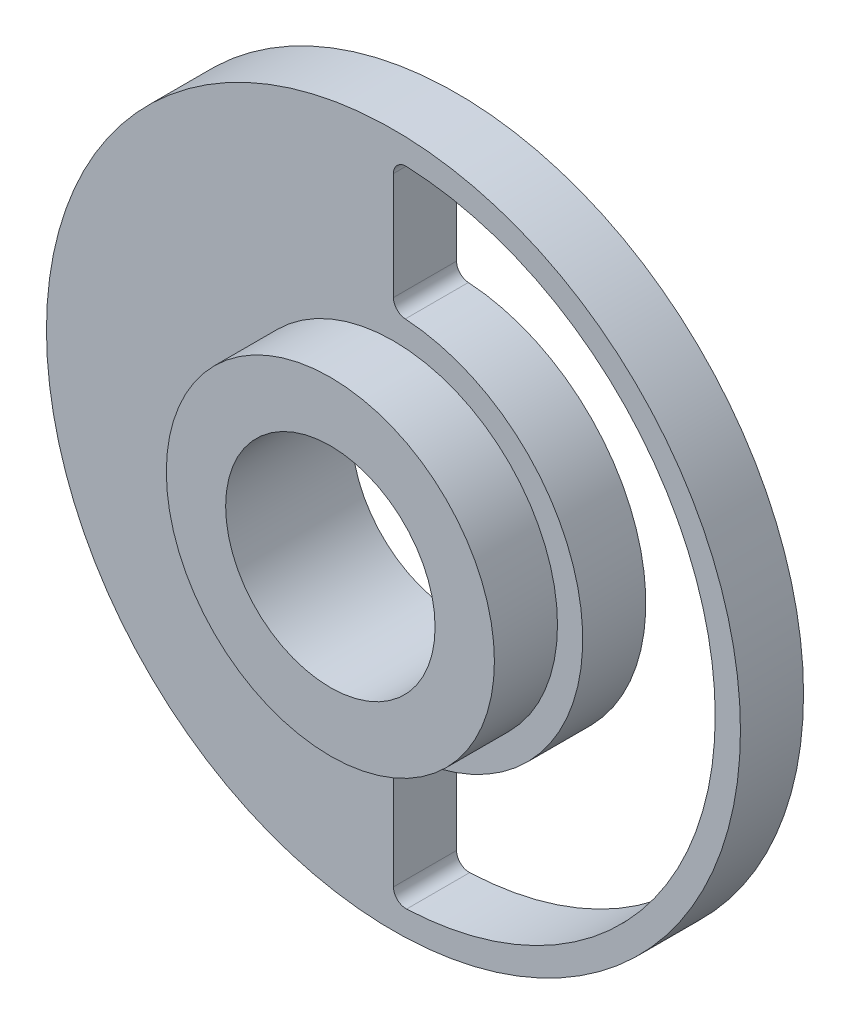
SolidWorks part; units mm, degrees
ref_plane "Front Plane" through (0, 0, 0) normal (0, 0, 1) x (1, 0, 0)
ref_plane "Top Plane" through (0, 0, 0) normal (0, 1, 0) x (1, 0, 0)
ref_plane "Right Plane" through (0, 0, 0) normal (1, 0, 0) x (0, 0, -1)
sketch "Sketch1" plane through (0, 0, 0) normal (0, 0, 1) x (1, 0, 0)
  circle A0 centre (0, 0) radius 4.15
  circle A1 centre (0, 0) radius 13.75
  dimension "D1" = 27.5
  dimension "D2" = 8.3
extrude "Boss-Extrude1" add sketch "Sketch1" along normal blind 2.5
sketch "Sketch2" plane through (0, 0, 2.5) normal (0, 0, 1) x (1, 0, 0)
  circle A0 centre (0, 0) radius 4.15
  circle A1 centre (0, 0) radius 6.5
  circle A2 centre (0, 0) radius 4.15 construction
  circle A3 centre (0, 0) radius 4 construction
  dimension "D1" = 8
  dimension "D2" = 2.5
extrude "Boss-Extrude2" add sketch "Sketch2" along normal blind 2.5
sketch "Sketch5" plane through (0, 0, 0) normal (0, 0, 1) x (1, 0, 0)
  line L0 (0, 0) -> (0, 7.5) construction
  line L1 (0, 7.5) -> (0, 12.75)
  line L2 (0, 0) -> (0, -7.5) construction
  line L3 (0, -7.5) -> (0, -12.75)
  circle A0 centre (0, 0) radius 12.75
  circle A1 centre (0, 0) radius 7.5
  circle A2 centre (0, 0) radius 13.75 construction
  circle A3 centre (0, 0) radius 6.5 construction
  dimension "D1" = 1
  dimension "D2" = 1
  dimension "D3" = 180
extrude "Cut-Extrude1" cut sketch "Sketch5" along normal through all contours A1 L3 A0 L1
fillet "Fillet1" radius 0.5 4 edges at (0, -7.5, 1.25) (0, -12.75, 1.25) (0, 7.5, 1.25) (0, 12.75, 1.25)
